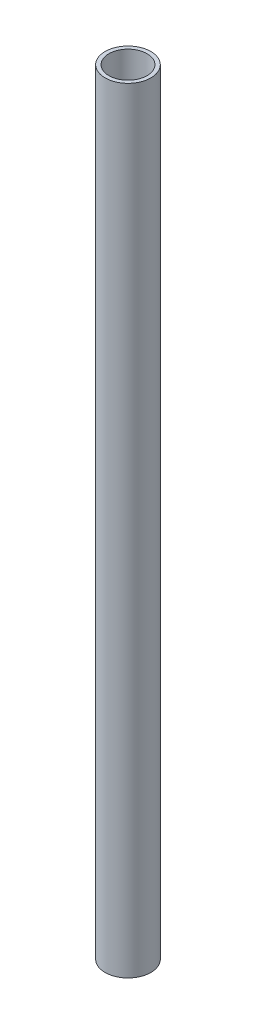
SolidWorks part; units mm, degrees
ref_plane "Front Plane" through (0, 0, 0) normal (0, 0, 1) x (1, 0, 0)
ref_plane "Top Plane" through (0, 0, 0) normal (0, 1, 0) x (1, 0, 0)
ref_plane "Right Plane" through (0, 0, 0) normal (1, 0, 0) x (0, 0, -1)
sketch "Sketch1" plane through (0, 0, 0) normal (0, 1, 0) x (1, 0, 0)
  circle A0 centre (0, 0) radius 5
  circle A1 centre (0, 0) radius 6
  dimension "D1" = 10
  dimension "D2" = 12
extrude "Boss-Extrude1" add sketch "Sketch1" along normal blind 203.2
